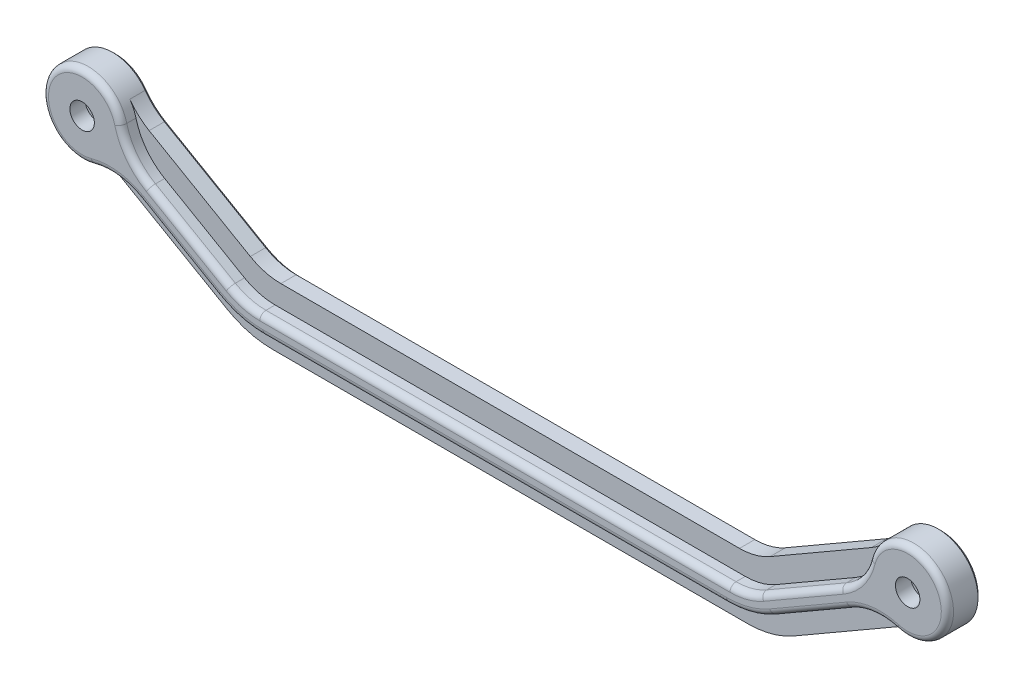
SolidWorks part; units mm, degrees
ref_plane "前视基准面" through (0, 0, 0) normal (0, 0, 1) x (1, 0, 0)
ref_plane "上视基准面" through (0, 0, 0) normal (0, 1, 0) x (1, 0, 0)
ref_plane "右视基准面" through (0, 0, 0) normal (1, 0, 0) x (0, 0, -1)
ref_plane "基准面1" through (0, 0, 5.5) normal (0, 0, 1) x (1, 0, 0)
sketch "草图1" plane through (0, 0, 5.5) normal (0, 0, 1) x (1, 0, 0)
  line L0 (-62.7728, -4.4613) -> (-41.9212, -16.5)
  line L1 (-41.9212, -16.5) -> (41.9212, -16.5)
  line L2 (41.9212, -16.5) -> (62.7728, -4.4613)
  line L3 (61.2728, -1.8632) -> (41.1173, -13.5)
  line L4 (41.1173, -13.5) -> (-41.1173, -13.5)
  line L5 (-41.1173, -13.5) -> (-61.2728, -1.8632)
  arc A0 (62.7728, -4.4613) -> (61.2728, -1.8632) centre (67.5, 0) ccw
  arc A1 (-61.2728, -1.8632) -> (-62.7728, -4.4613) centre (-67.5, 0) ccw
extrude "凸台-拉伸1" add sketch "草图1" against normal blind 2.5
sketch "草图2" plane through (0, 0, 3) normal (0, 0, -1) x (-1, 0, 0)
  line L0 (66.4031, -6.4068) -> (42.859, -20)
  line L1 (42.859, -20) -> (-42.859, -20)
  line L2 (-42.859, -20) -> (-66.4031, -6.4068)
  line L3 (-61.4031, 2.2535) -> (-40.1795, -10)
  line L4 (-40.1795, -10) -> (40.1795, -10)
  line L5 (40.1795, -10) -> (61.4031, 2.2535)
  arc A0 (61.4031, 2.2535) -> (66.4031, -6.4068) centre (67.5, 0) cw
  arc A1 (-66.4031, -6.4068) -> (-61.4031, 2.2535) centre (-67.5, 0) cw
extrude "凸台-拉伸2" add sketch "草图2" along normal blind 3
hole_wizard "Ø4.0 (4) 直径孔1" positions "草图4" profile "草图3" hole size "Ø4.0" standard "ANSI Metric"
sketch "草图4" plane through (0, 0, 0) normal (0, 0, -1) x (-1, 0, 0)
  point P0 (67.5, 0)
  point P1 (-67.5, 0)
sketch "草图3" plane through (-67.5, 0, 0) normal (1, 0, 0) x (0, 1, 0)
  line L0 (0, 0) -> (0, 5.5)
  line L1 (0, 5.5) -> (2, 5.5)
  line L2 (2, 5.5) -> (2, 0)
  line L5 (2, 0) -> (0, 0)
  line L11 (0, -6.35) -> (0, 107.95) construction
  dimension "通孔孔直径" = 4
  dimension "通孔孔深度" = 5.5
fillet "圆角1" radius 10 12 edges at (40.1795, -10, 1.5) (-61.4031, 2.2535, 1.5) (66.4031, -6.4068, 1.5) (61.2728, -1.8632, 4.25) (-41.1173, -13.5, 4.25) (-61.2728, -1.8632, 4.25) (-40.1795, -10, 1.5) (-62.7728, -4.4613, 4.25) (61.4031, 2.2535, 1.5) (62.7728, -4.4613, 4.25) (41.1173, -13.5, 4.25) (-66.4031, -6.4068, 1.5)
fillet "圆角2" radius 15 4 edges at (-42.859, -20, 1.5) (41.9212, -16.5, 4.25) (-41.9212, -16.5, 4.25) (42.859, -20, 1.5)
chamfer "倒角1" distance 0.5 angle 45 16 edges at (66.0084, -6.9002, 0) (55.1934, -12.8787, 0) (73.1292, 3.25, 0) (42.722, -19.4889, 0) (60.7785, 2.1583, 0) (0, -20, 0) (50.7735, -3.8835, 0) (-42.722, -19.4889, 0) (40.0882, -9.6593, 0) (-55.1934, -12.8787, 0) (0, -10, 0) (-66.0084, -6.9002, 0) (-40.0882, -9.6593, 0) (-73.1292, 3.25, 0) (-50.7735, -3.8835, 0) (-60.7785, 2.1583, 0)
fillet "圆角4" radius 1 16 edges at (41.026, -13.1593, 5.5) (49.9704, -8.3886, 5.5) (0, -13.5, 5.5) (59.4797, -1.9878, 5.5) (-41.026, -13.1593, 5.5) (73.1292, 3.25, 5.5) (-49.9704, -8.3886, 5.5) (61.7684, -5.9519, 5.5) (-59.4797, -1.9878, 5.5) (51.7025, -10.8527, 5.5) (-73.1292, 3.25, 5.5) (41.7842, -15.9889, 5.5) (-61.7684, -5.9519, 5.5) (0, -16.5, 5.5) (-51.7025, -10.8527, 5.5) (-41.7842, -15.9889, 5.5)
sketch "草图5" plane through (0, 0, 0) normal (0, 0, -1) x (-1, 0, 0)
  line L6 (-63.7971, -7.334) -> (-46.0897, -17.5574)
  line L7 (-38.8397, -19.5) -> (38.8397, -19.5)
  line L8 (46.0897, -17.5574) -> (63.7971, -7.334)
  line L9 (59.2971, 0.4602) -> (42.75, -9.0933)
  line L10 (37.5, -10.5) -> (-37.5, -10.5)
  line L11 (-42.75, -9.0933) -> (-59.2971, 0.4602)
  line L12 (-63.7971, -7.334) -> (-46.0897, -17.5574)
  line L13 (-38.8397, -19.5) -> (38.8397, -19.5)
  line L14 (46.0897, -17.5574) -> (63.7971, -7.334)
  line L15 (59.2971, 0.4602) -> (42.75, -9.0933)
  line L16 (37.5, -10.5) -> (-37.5, -10.5)
  line L17 (-42.75, -9.0933) -> (-59.2971, 0.4602)
  circle A0 centre (67.5, 0) radius 2 construction
  circle A1 centre (-67.5, 0) radius 2 construction
  circle A2 centre (67.5, 0) radius 2
  circle A3 centre (-67.5, 0) radius 2
  arc A10 (-62.608, 3.474) -> (-68.0626, -5.9736) centre (-67.5, 0) ccw
  arc A11 (-63.7971, -7.334) -> (-68.0626, -5.9736) centre (-69.0471, -16.4273) ccw
  arc A12 (-46.0897, -17.5574) -> (-38.8397, -19.5) centre (-38.8397, -5) ccw
  arc A13 (38.8397, -19.5) -> (46.0897, -17.5574) centre (38.8397, -5) ccw
  arc A14 (68.0626, -5.9736) -> (63.7971, -7.334) centre (69.0471, -16.4273) ccw
  arc A15 (68.0626, -5.9736) -> (62.608, 3.474) centre (67.5, 0) ccw
  arc A16 (59.2971, 0.4602) -> (62.608, 3.474) centre (54.0471, 9.5534) ccw
  arc A17 (37.5, -10.5) -> (42.75, -9.0933) centre (37.5, 0) ccw
  arc A18 (-42.75, -9.0933) -> (-37.5, -10.5) centre (-37.5, 0) ccw
  arc A19 (-62.608, 3.474) -> (-59.2971, 0.4602) centre (-54.0471, 9.5534) ccw
  arc A20 (-62.608, 3.474) -> (-68.0626, -5.9736) centre (-67.5, 0) ccw
  arc A21 (-63.7971, -7.334) -> (-68.0626, -5.9736) centre (-69.0471, -16.4273) ccw
  arc A22 (-46.0897, -17.5574) -> (-38.8397, -19.5) centre (-38.8397, -5) ccw
  arc A23 (38.8397, -19.5) -> (46.0897, -17.5574) centre (38.8397, -5) ccw
  arc A24 (68.0626, -5.9736) -> (63.7971, -7.334) centre (69.0471, -16.4273) ccw
  arc A25 (68.0626, -5.9736) -> (62.608, 3.474) centre (67.5, 0) ccw
  arc A26 (59.2971, 0.4602) -> (62.608, 3.474) centre (54.0471, 9.5534) ccw
  arc A27 (37.5, -10.5) -> (42.75, -9.0933) centre (37.5, 0) ccw
  arc A28 (-42.75, -9.0933) -> (-37.5, -10.5) centre (-37.5, 0) ccw
  arc A29 (-62.608, 3.474) -> (-59.2971, 0.4602) centre (-54.0471, 9.5534) ccw
  circle M33 centre (67.5, 0) radius 2
  circle M34 centre (-67.5, 0) radius 2
  dimension "D1" = 0
extrude "凸台-拉伸3" add sketch "草图5" against normal blind 3 contours M33 | M34
